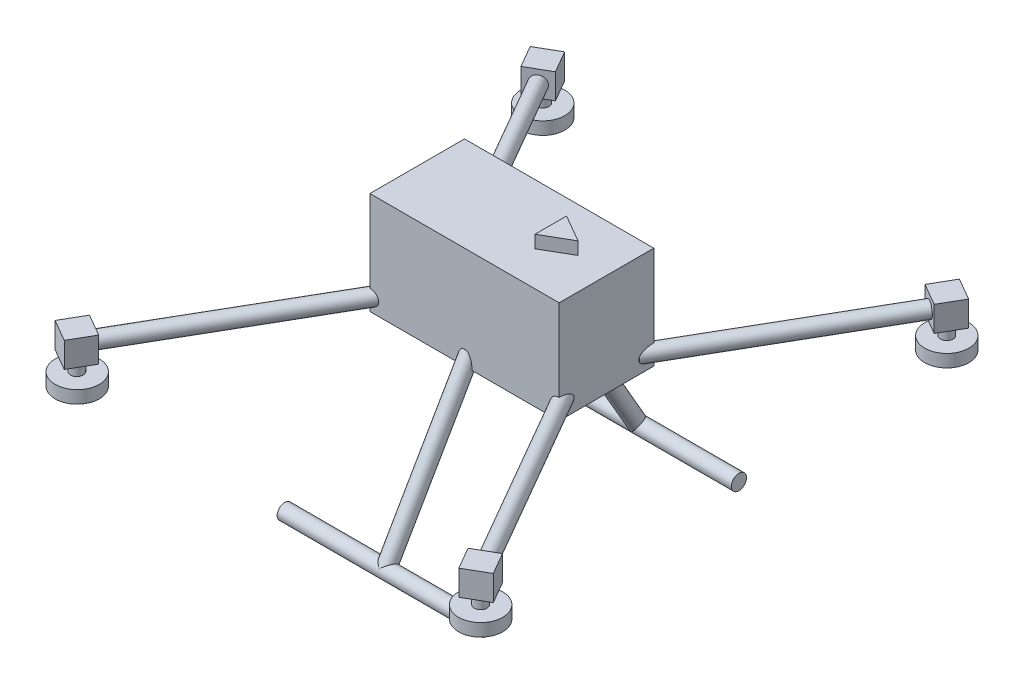
SolidWorks part; units mm, degrees
other "M300"
ref_plane "前视基准面" through (0, 0, 0) normal (0, 0, 1) x (1, 0, 0)
ref_plane "上视基准面" through (0, 0, 0) normal (0, 1, 0) x (1, 0, 0)
ref_plane "右视基准面" through (0, 0, 0) normal (1, 0, 0) x (0, 0, -1)
sketch "草图9" plane through (0, 0, 0) normal (0, 1, 0) x (1, 0, 0)
  line L1 (150, -75) -> (-150, -75)
  line L2 (150, -75) -> (150, 75)
  line L3 (150, 75) -> (-150, 75)
  line L4 (-150, -75) -> (-150, 75)
  line L5 (150, -75) -> (-150, 75) construction
  line L6 (150, 75) -> (-150, -75) construction
  point P0 (0, 0)
  dimension "D1" = 300
  dimension "D2" = 150
extrude "凸台-拉伸2" add sketch "草图9" along normal blind 162
ref_plane "基准面2" through (-69.976, 0, 121.2019) normal (-0.5, 0, 0.866) x (0, -1, 0)
sketch "草图10" plane through (-69.976, 0, 121.2019) normal (-0.5, 0, 0.866) x (0, -1, 0)
  line L0 (0, -92.4038) -> (-20, -92.4038)
  line L1 (-162, -92.4038) -> (0, -92.4038) construction
  circle A0 centre (-20, -92.4038) radius 12
  dimension "D2" = 24
  dimension "D1" = 20
extrude "凸台-拉伸3" add sketch "草图10" along normal blind 340 and the other way blind 20 contours A0
ref_plane "基准面3" through (-69.976, 0, -121.2019) normal (-0.5, 0, -0.866) x (0, -1, 0)
sketch "草图11" plane through (-69.976, 0, -121.2019) normal (-0.5, 0, -0.866) x (0, -1, 0)
  line L0 (0, 92.4038) -> (-20, 92.4038)
  line L2 (-162, 92.4038) -> (0, 92.4038) construction
  circle A0 centre (-20, 92.4038) radius 12
  dimension "D2" = 24
  dimension "D1" = 20
extrude "凸台-拉伸4" add sketch "草图11" along normal blind 338.9185 and the other way blind 20 contours A0
ref_plane "基准面4" through (69.976, 0, -121.2019) normal (0.5, 0, -0.866) x (0, -1, 0)
ref_plane "基准面5" through (69.976, 0, 121.2019) normal (0.5, 0, 0.866) x (0, -1, 0)
sketch "草图12" plane through (69.976, 0, -121.2019) normal (0.5, 0, -0.866) x (0, -1, 0)
  line L0 (0, -92.4038) -> (-20, -92.4038)
  line L2 (0, -92.4038) -> (0, 167.4038) construction
  line L3 (-162, -92.4038) -> (0, -92.4038) construction
  circle A0 centre (-20, -92.4038) radius 12
  dimension "D2" = 24
  dimension "D1" = 20
sketch "草图13" plane through (69.976, 0, 121.2019) normal (0.5, 0, 0.866) x (0, -1, 0)
  line L0 (0, 92.4038) -> (-20, 92.4038)
  line L2 (-162, 92.4038) -> (0, 92.4038) construction
  circle A0 centre (-20, 92.4038) radius 12
  dimension "D2" = 24
  dimension "D1" = 20
extrude "凸台-拉伸5" add sketch "草图13" along normal blind 340 and the other way blind 20 contours A0
extrude "凸台-拉伸6" add sketch "草图12" along normal blind 340 and the other way blind 20 contours A0
ref_plane "基准面7" through (-239.976, 0, 415.6505) normal (-0.5, 0, 0.866) x (0.866, 0, 0.5)
sketch "草图14" plane through (-239.976, 0, 415.6505) normal (-0.5, 0, 0.866) x (0.866, 0, 0.5)
  line L0 (-92.4038, 0) -> (167.4038, 0) construction
  line L1 (-112.4038, 40) -> (-72.4038, 40)
  line L2 (-112.4038, 40) -> (-112.4038, 0)
  line L3 (-112.4038, 0) -> (-72.4038, 0)
  line L4 (-72.4038, 40) -> (-72.4038, 0)
  line L5 (-112.4038, 40) -> (-72.4038, 0) construction
  line L6 (-112.4038, 0) -> (-72.4038, 40) construction
  line L7 (376.5526, 0) -> (-376.5526, 0) construction
  point P0 (-92.4038, 20)
extrude "凸台-拉伸7" add sketch "草图14" along normal blind 20 and the other way blind 20 contours L2 L3 L4 L1
ref_plane "基准面8" through (-239.4352, 0, -414.7139) normal (-0.5, 0, -0.866) x (-0.866, 0, 0.5)
ref_plane "基准面9" through (239.976, 0, -415.6505) normal (0.5, 0, -0.866) x (-0.866, 0, -0.5)
ref_plane "基准面10" through (239.976, 0, 415.6505) normal (0.5, 0, 0.866) x (0.866, 0, -0.5)
sketch "草图17" plane through (-239.4352, 0, -414.7139) normal (-0.5, 0, -0.866) x (-0.866, 0, 0.5)
  line L1 (72.4038, 40) -> (112.4038, 40)
  line L2 (72.4038, 40) -> (72.4038, 0)
  line L3 (72.4038, 0) -> (112.4038, 0)
  line L4 (112.4038, 40) -> (112.4038, 0)
  line L5 (72.4038, 40) -> (112.4038, 0) construction
  line L6 (72.4038, 0) -> (112.4038, 40) construction
  line L8 (92.4038, 162) -> (92.4038, 32) construction
  line L9 (372.742, 0) -> (-372.742, 0) construction
  line L10 (489.173, 40) -> (489.173, 0) construction
  point P0 (92.4038, 20)
sketch "草图18" plane through (239.976, 0, -415.6505) normal (0.5, 0, -0.866) x (-0.866, 0, -0.5)
  line L1 (-112.4038, 40) -> (-72.4038, 40)
  line L2 (-112.4038, 40) -> (-112.4038, 0)
  line L3 (-112.4038, 0) -> (-72.4038, 0)
  line L4 (-72.4038, 40) -> (-72.4038, 0)
  line L5 (-112.4038, 40) -> (-72.4038, 0) construction
  line L6 (-112.4038, 0) -> (-72.4038, 40) construction
  line L8 (376.5526, 0) -> (-376.5526, 0) construction
  line L9 (-92.4038, 162) -> (-92.4038, 32) construction
  line L10 (112.4038, 40) -> (112.4038, 0) construction
  point P0 (-92.4038, 20)
sketch "草图20" plane through (239.976, 0, 415.6505) normal (0.5, 0, 0.866) x (0.866, 0, -0.5)
  line L0 (72.4038, 40) -> (112.4038, 40)
  line L1 (72.4038, 40) -> (72.4038, 0)
  line L2 (72.4038, 0) -> (112.4038, 0)
  line L3 (112.4038, 40) -> (112.4038, 0)
  line L4 (72.4038, 40) -> (112.4038, 0) construction
  line L5 (72.4038, 0) -> (112.4038, 40) construction
  line L6 (376.5526, 0) -> (-376.5526, 0) construction
  line L7 (92.4038, 162) -> (92.4038, 32) construction
  line L8 (-469.173, 40) -> (-469.173, 0) construction
  point P0 (92.4038, 20)
extrude "凸台-拉伸8" add sketch "草图17" along normal blind 20 and the other way blind 20
extrude "凸台-拉伸9" add sketch "草图18" along normal blind 20 and the other way blind 20
extrude "凸台-拉伸10" add sketch "草图20" along normal blind 20 and the other way blind 20
sketch "草图21" plane through (0, 0, 0) normal (0, -1, 0) x (1, 0, 0)
  line L0 (-347.3205, 376.7691) -> (-292.6795, 362.1281) construction
  line L1 (-312.6795, 396.7691) -> (-327.3205, 342.1281) construction
  line L2 (-326.7798, -341.1915) -> (-312.1387, -395.8325) construction
  line L3 (-346.7798, -375.8325) -> (-292.1387, -361.1915) construction
  line L4 (292.6795, -362.1281) -> (347.3205, -376.7691) construction
  line L5 (327.3205, -342.1281) -> (312.6795, -396.7691) construction
  line L6 (327.3205, 342.1281) -> (312.6795, 396.7691) construction
  line L7 (292.6795, 362.1281) -> (347.3205, 376.7691) construction
  circle A0 centre (-320, 369.4486) radius 10
  circle A1 centre (-319.4593, -368.512) radius 10
  circle A2 centre (320, -369.4486) radius 10
  circle A3 centre (320, 369.4486) radius 10
  dimension "D1" = 20
  dimension "D2" = 20
  dimension "D3" = 20
  dimension "D4" = 20
extrude "凸台-拉伸11" add sketch "草图21" along normal blind 20 and the other way blind 20
sketch "草图22" plane through (0, -20, 0) normal (0, -1, 0) x (1, 0, 0)
  circle A0 centre (-319.4593, -368.512) radius 35
  circle A1 centre (320, -369.4486) radius 35
  circle A2 centre (320, 369.4486) radius 35
  circle A3 centre (-319.4593, 369.4486) radius 35
  dimension "D1" = 70
  dimension "D2" = 70
  dimension "D3" = 70
  dimension "D4" = 70
extrude "凸台-拉伸12" add sketch "草图22" along normal blind 20
ref_plane "基准面13" through (0, -32.476, 18.75) normal (0, -0.866, 0.5) x (1, 0, 0)
sketch "草图23" plane through (0, -32.476, 18.75) normal (0, -0.866, 0.5) x (1, 0, 0)
  line L0 (-150, 64.9519) -> (150, 64.9519) construction
  circle A0 centre (0, 64.9519) radius 12
  dimension "D1" = 24
extrude "凸台-拉伸13" add sketch "草图23" along normal blind 250 and the other way blind 20
ref_plane "基准面14" through (0, -32.476, -18.75) normal (0, -0.866, -0.5) x (-1, 0, 0)
sketch "草图24" plane through (0, -32.476, -18.75) normal (0, -0.866, -0.5) x (-1, 0, 0)
  line L0 (-150, 64.9519) -> (150, 64.9519) construction
  circle A0 centre (0, 64.9519) radius 12
  dimension "D1" = 24
extrude "凸台-拉伸14" add sketch "草图24" along normal blind 250 and the other way blind 20
sketch "草图26" plane through (0, 162, 0) normal (0, 1, 0) x (1, 0, 0)
  line L0 (100, 5.0021) -> (56.6987, 30.0021)
  line L1 (56.6987, 30.0021) -> (56.6987, -19.9979)
  line L2 (56.6987, -19.9979) -> (100, 5.0021)
  line L3 (100, 5.0021) -> (150, 5.0021) construction
  line L4 (150, -75) -> (150, 75) construction
  dimension "D1" = 50
  dimension "D2" = 50
extrude "凸台-拉伸15" add sketch "草图26" along normal blind 20 and the other way blind 20
sketch "草图27" plane through (0, -248.9823, -143.75) normal (0, -0.866, -0.5) x (1, 0, 0)
  point P0 (0, -64.9519)
ref_plane "基准面17" through (0, 0, 0) normal (-1, 0, 0) x (0, 0, 1)
sketch "草图29" plane through (0, 0, 0) normal (-1, 0, 0) x (0, 0, 1)
  line L0 (189.6077, -222.5064) -> (210.3923, -210.5064) construction
  circle A0 centre (-200, -216.5064) radius 12
  circle A1 centre (200, -216.5064) radius 12
  dimension "D1" = 24
  dimension "D2" = 24
extrude "凸台-拉伸16" add sketch "草图29" along normal blind 160 and the other way blind 160
